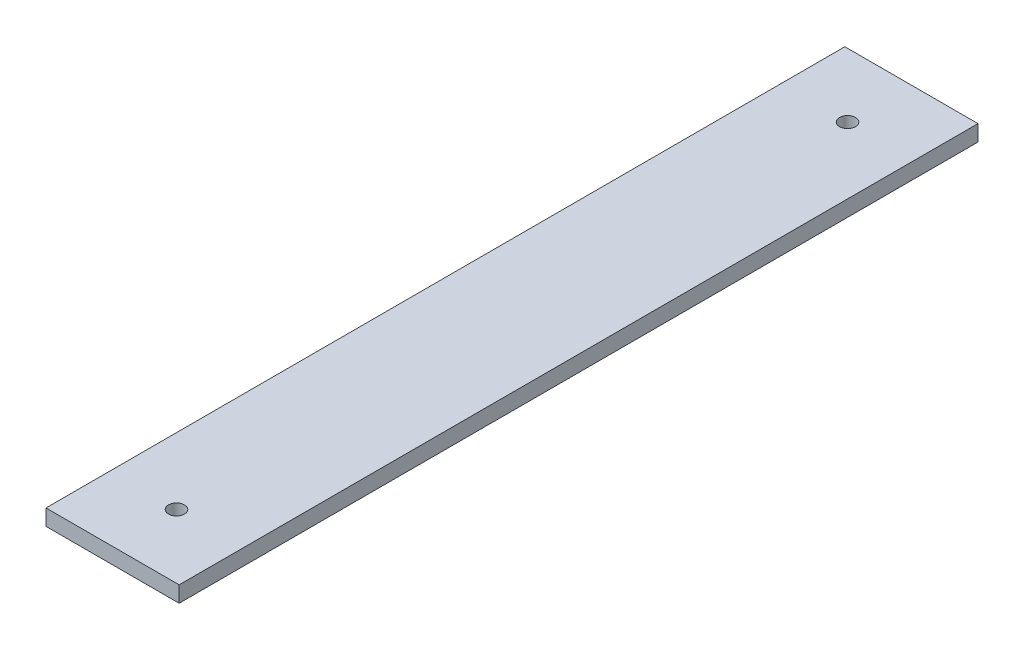
SolidWorks part; units mm, degrees
ref_plane "Front Plane" through (0, 0, 0) normal (0, 0, 1) x (1, 0, 0)
ref_plane "Top Plane" through (0, 0, 0) normal (0, 1, 0) x (1, 0, 0)
ref_plane "Right Plane" through (0, 0, 0) normal (1, 0, 0) x (0, 0, -1)
sketch "Sketch2" plane through (0, 0, 0) normal (0, 1, 0) x (1, 0, 0)
  line L1 (-12.5, 75) -> (12.5, 75)
  line L2 (-12.5, 75) -> (-12.5, -75)
  line L3 (-12.5, -75) -> (12.5, -75)
  line L4 (12.5, 75) -> (12.5, -75)
  line L5 (-12.5, 75) -> (12.5, -75) construction
  line L6 (-12.5, -75) -> (12.5, 75) construction
  point P0 (0, 0)
  dimension "D1" = 150
  dimension "D2" = 25
extrude "Boss-Extrude1" add sketch "Sketch2" along normal blind 3
sketch "Sketch3" plane through (0, 3, 0) normal (0, 1, 0) x (1, 0, 0)
  line L0 (12.5, 75) -> (-12.5, 75) construction
  line L1 (-12.5, 75) -> (-12.5, -75) construction
  circle A0 centre (0, 63) radius 1.5
  point P4 (0, 0)
  dimension "D1" = 12
  dimension "D2" = 12.5
extrude "Cut-Extrude1" cut sketch "Sketch3" against normal blind 11
mirror "Mirror1" about plane through (0, 0, 0) normal (0, 0, 1) of "Cut-Extrude1"
